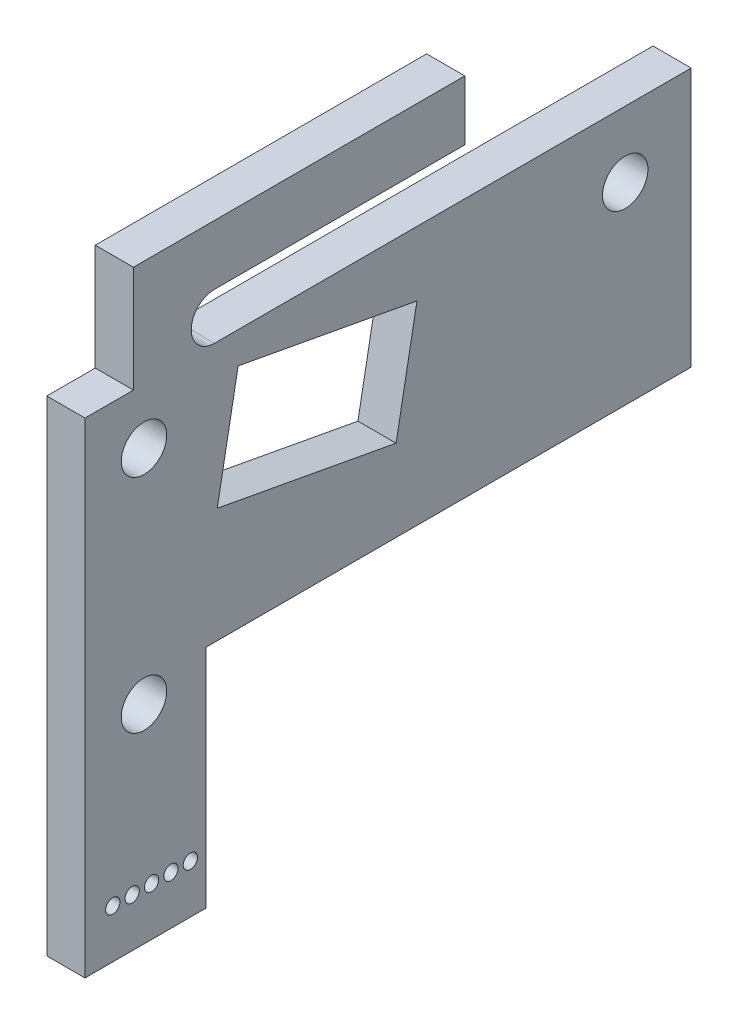
SolidWorks part; units mm, degrees
material "Hardboard"
ref_plane "Front Plane" through (0, 0, 0) normal (0, 0, 1) x (1, 0, 0)
ref_plane "Top Plane" through (0, 0, 0) normal (0, 1, 0) x (1, 0, 0)
ref_plane "Right Plane" through (0, 0, 0) normal (1, 0, 0) x (0, 0, -1)
sketch "Sketch1" plane through (0, 0, 0) normal (1, 0, 0) x (0, 0, -1)
  line L0 (-56.5904, 6.9096) -> (-51.5186, 6.9096)
  line L1 (-56.5904, 6.9096) -> (-56.5904, -43.8904)
  line L2 (-56.5904, -43.8904) -> (-43.8904, -43.8904)
  line L3 (-43.8904, -43.8904) -> (-43.8904, -20.2221)
  line L4 (-43.8904, -20.2221) -> (6.9096, -20.2221)
  line L5 (6.9096, -20.2221) -> (6.9096, 6.9096)
  line L6 (0, 6.9096) -> (0, 0) construction
  line L7 (6.9096, 0) -> (0, 0) construction
  line L8 (-40.5479, 3.6124) -> (-21.8156, 0.1475)
  line L9 (-40.5479, 3.6124) -> (-42.7334, -8.2033)
  line L10 (-21.8156, 0.1475) -> (-24.0012, -11.6682)
  line L11 (-42.7334, -8.2033) -> (-24.0012, -11.6682)
  line L12 (-45.553, -38.8104) -> (-47.585, -38.8104) construction
  line L13 (-43.0185, 11.7973) -> (-16.804, 11.7973)
  line L14 (-16.804, 11.7973) -> (-16.804, 18.0537)
  line L15 (-16.804, 18.0537) -> (-51.5186, 18.0537)
  line L16 (-51.5186, 18.0537) -> (-51.5186, 6.9096)
  line L17 (-43.0185, 6.9096) -> (6.9096, 6.9096)
  line L18 (-43.0916, -6.1748) -> (-43.04, 6.5251) construction
  circle A0 centre (0, 0) radius 2.3813
  circle A1 centre (-45.553, -38.8104) radius 0.75
  circle A2 centre (-47.585, -38.8104) radius 0.75
  circle A3 centre (-49.617, -38.8104) radius 0.75
  circle A4 centre (-51.649, -38.8104) radius 0.75
  circle A5 centre (-50.4101, -22.1372) radius 2.3812
  circle A6 centre (-50.4101, 1.0794) radius 2.3812
  circle A7 centre (-53.681, -38.8104) radius 0.75
  arc A8 (-43.0185, 6.9096) -> (-43.0185, 11.7973) centre (-43.0185, 9.3535) cw
  dimension "D1" = 4.7625
  dimension "D2" = 1.5
  dimension "D3" = 5.08
  dimension "D5" = 2.032
  dimension "D6" = 19.05
  dimension "D4" = 5
extrude "Boss-Extrude1" add sketch "Sketch1" along normal mid plane 4
